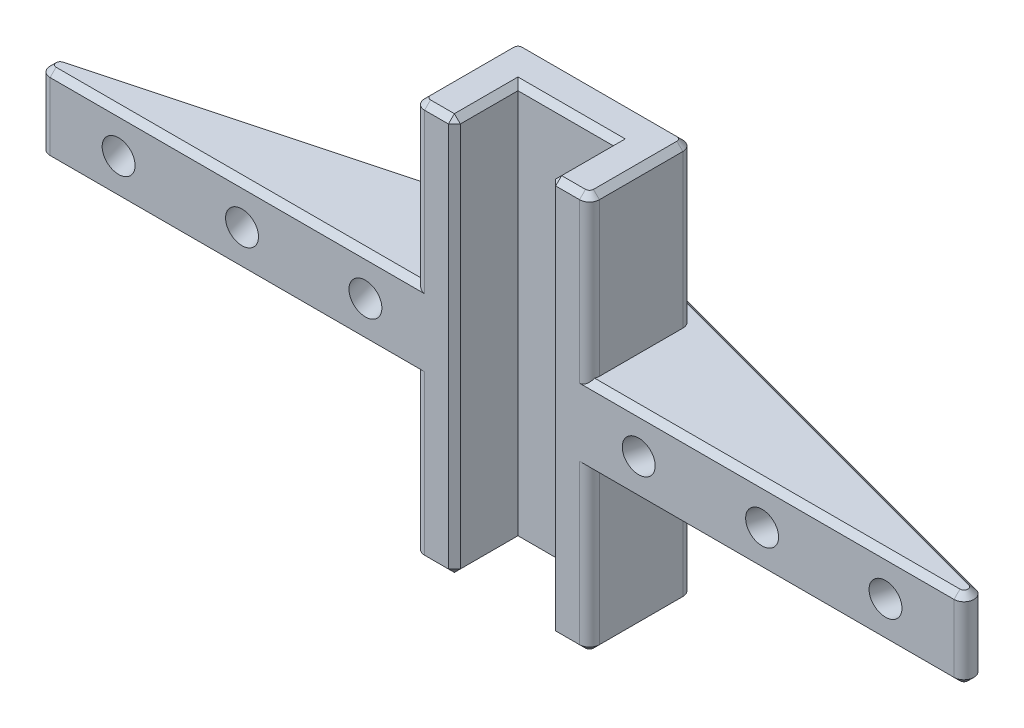
SolidWorks part; units mm, degrees
ref_plane "Front Plane" through (0, 0, 0) normal (0, 0, 1) x (1, 0, 0)
ref_plane "Top Plane" through (0, 0, 0) normal (0, 1, 0) x (1, 0, 0)
ref_plane "Right Plane" through (0, 0, 0) normal (1, 0, 0) x (0, 0, -1)
sketch "Sketch1" plane through (0, 0, 0) normal (0, 1, 0) x (1, 0, 0)
  line L0 (12, 0) -> (-12, 0)
  line L1 (-12, 0) -> (-12, -16)
  line L2 (-12, -16) -> (-132.7407, -16)
  line L3 (-132.7407, -16) -> (-12, 16.3524)
  line L4 (-12, 16.3524) -> (12, 16.3524)
  line L5 (0, 16.3524) -> (0, 0) construction
  line L6 (132.7407, -16) -> (12, 16.3524)
  line L7 (12, -16) -> (132.7407, -16)
  line L8 (12, 0) -> (12, -16)
  dimension "D1" = 24
  dimension "D2" = 16
  dimension "D3" = 15
  dimension "D4" = 125
extrude "Boss-Extrude1" add sketch "Sketch1" along normal mid plane 20
sketch "Sketch2" plane through (0, 0, 0) normal (0, 1, 0) x (1, 0, 0)
  line L0 (-12, -16) -> (-12, 0) construction
  line L1 (-12, 0) -> (12, 0) construction
  line L2 (12, 0) -> (12, -16) construction
  line L3 (-12, -16) -> (-12, 0)
  line L4 (-12, 0) -> (12, 0)
  line L5 (12, 0) -> (12, -16)
  line L6 (-22, -16) -> (-22, 10)
  line L7 (-22, 10) -> (22, 10)
  line L8 (22, 10) -> (22, -16)
  line L9 (-22, -16) -> (-12, -16)
  line L10 (12, -16) -> (22, -16)
  dimension "D1" = 10
extrude "Boss-Extrude2" add sketch "Sketch2" along normal mid plane 100
hole_wizard "Ø8.0mm Dowel Hole1" positions "Sketch6" profile "Sketch5" hole size "Ø8.0" standard "ANSI Metric" end condition through all
sketch "Sketch6" plane through (4.8919, 0, -18.257) normal (0.2588, 0, -0.9659) x (-0.9659, 0, -0.2588)
  line L2 (-132.3588, 0) -> (-97.3588, 0) construction
  line L3 (-132.3588, 10) -> (-132.3588, -10) construction
  line L4 (-97.3588, 0) -> (-67.3588, 0) construction
  line L5 (-67.3588, 0) -> (-37.3588, 0) construction
  line L6 (-37.3588, 0) -> (0, 0) construction
  point P22 (-97.3588, 0)
  point P24 (-67.3588, 0)
  point P26 (-37.3588, 0)
  dimension "D2" = 35
  dimension "D1" = 30
sketch "Sketch5" plane through (98.9333, 0, 6.9413) normal (0, 1, 0) x (-0.9659, 0, -0.2588)
  line L0 (0, 0) -> (0, 68.7117)
  line L1 (0, 68.7117) -> (4, 68.7117)
  line L2 (4, 68.7117) -> (4, 0)
  line L5 (4, 0) -> (0, 0)
  line L11 (0, -6.35) -> (0, 107.95) construction
  dimension "Thru Hole Dia." = 8
  dimension "Thru Hole Depth" = 68.7117
mirror "Mirror1" about plane through (0, 0, 0) normal (1, 0, 0) of "Ø8.0mm Dowel Hole1"
fillet "Fillet1" radius 2.5 12 edges at (132.7407, 0, 16) (-132.7407, 0, 16) (-22, -30, 16) (-22, 30, 16) (22, -30, 16) (22, 30, 16) (22, 30, -10) (22, -30, -10) (-22, -30, -10) (-22, 30, -10) (12, 0, -16.3524) (-12, 0, -16.3524)
chamfer "Chamfer1" distance 1.5 angle 45 44 edges at (-15.75, -50, 16) (-21.2678, -50, 15.2678) (-22, -50, 3) (-21.2678, -50, -9.2678) (15.75, -50, 16) (0, -50, -10) (21.2678, -50, 15.2678) (21.2678, -50, -9.2678) (22, -50, 3) (-66.6257, -10, 16) (-116.23, -10, 13.8263) (-63.3582, -10, -2.591) (-11.9972, -10, -16.331) (0, -10, -16.3524) (11.9972, -10, -16.331) (63.3582, -10, -2.591) (116.23, -10, 13.8263) (66.6257, -10, 16) (12, 0, 16) (12, -50, 8) (0, -50, 0) (-12, -50, 8) (-12, 0, 16) (-12, 50, 8) (12, 50, 8) (0, 50, 0) (15.75, 50, 16) (-15.75, 50, 16) (21.2678, 50, 15.2678) (-21.2678, 50, 15.2678) (22, 50, 3) (-22, 50, 3) (21.2678, 50, -9.2678) (-21.2678, 50, -9.2678) (0, 50, -10) (-66.6257, 10, 16) (-116.23, 10, 13.8263) (-63.3582, 10, -2.591) (-11.9972, 10, -16.331) (66.6257, 10, 16) (0, 10, -16.3524) (116.23, 10, 13.8263) (11.9972, 10, -16.331) (63.3582, 10, -2.591)
hole_wizard "CBORE for M5 SHCS1" positions "Sketch7" profile "Sketch8" counterbore size "M5" standard "ANSI Metric" end condition through all
sketch "Sketch7" plane through (0, 0, -10) normal (0, 0, -1) x (-1, 0, 0)
  line L0 (0, 38) -> (0, 0) construction
  line L1 (0, 0) -> (24.398, 0) construction
  line L3 (-19.5, 50) -> (19.5, 50) construction
  point P0 (0, 38)
  point P10 (0, -38)
  dimension "D1" = 12
sketch "Sketch8" plane through (0, 38, -10) normal (1, 0, 0) x (0, 1, 0)
  line L0 (0, 0) -> (0, 26)
  line L1 (0, 26) -> (2.75, 26)
  line L3 (2.75, 26) -> (2.75, 5)
  line L4 (2.75, 5) -> (5, 5)
  line L5 (5, 5) -> (5, 0)
  line L7 (5, 0) -> (0, 0)
  line L11 (0, -6.35) -> (0, 107.95) construction
  dimension "Thru Hole Dia." = 5.5
  dimension "Thru Hole Depth" = 26
  dimension "C'Bore Dia." = 10
  dimension "C'Bore Depth" = 5
sketch "Sketch9" plane through (0, 0, 0) normal (0, 0, 1) x (1, 0, 0)
  circle A0 centre (0, -38) radius 2.75 construction
  circle A1 centre (0, 38) radius 2.75 construction
  circle A2 centre (0, -38) radius 2.75
  circle A3 centre (0, 38) radius 2.75
extrude "Boss-Extrude3" add sketch "Sketch9" against normal blind 0.4
chamfer "Chamfer2" distance 1 angle 60 6 edges at (-102.797, 0, 7.9766) (-73.8193, 0, 0.212) (-44.8415, 0, -7.5525) (37.1141, 0, -9.6231) (66.0918, 0, -1.8585) (95.0696, 0, 5.9061)
